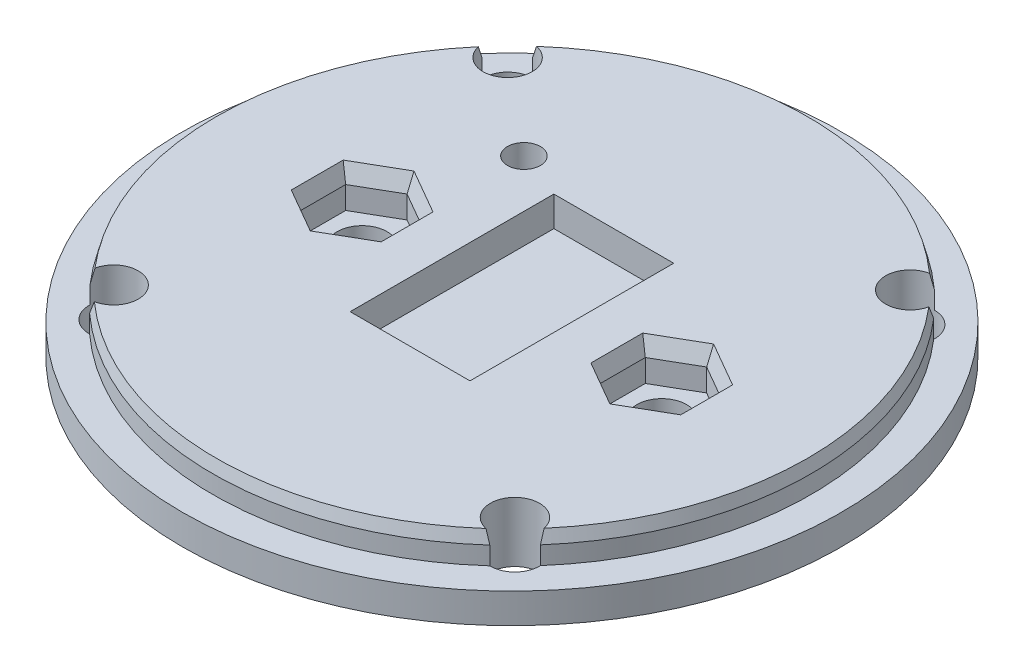
SolidWorks part; units mm, degrees
ref_plane "Спереди" through (0, 0, 0) normal (0, 0, 1) x (1, 0, 0)
ref_plane "Сверху" through (0, 0, 0) normal (0, 1, 0) x (1, 0, 0)
ref_plane "Справа" through (0, 0, 0) normal (1, 0, 0) x (0, 0, -1)
sketch "Эскиз1" plane through (0, 0, 0) normal (0, 1, 0) x (1, 0, 0)
  circle A0 centre (0, 0) radius 55
  dimension "D1" = 110
extrude "Бобышка-Вытянуть1" add sketch "Эскиз1" along normal blind 5
sketch "Эскиз2" plane through (0, 5, 0) normal (0, 1, 0) x (1, 0, 0)
  circle A0 centre (0, 0) radius 49.9
  dimension "D1" = 99.8
extrude "Бобышка-Вытянуть2" add sketch "Эскиз2" along normal blind 5
sketch "Эскиз3" plane through (0, 0, 0) normal (0, -1, 0) x (1, 0, 0)
  line L1 (17.5, -15) -> (-17.5, -15)
  line L2 (17.5, -15) -> (17.5, 15)
  line L3 (17.5, 15) -> (-17.5, 15)
  line L4 (-17.5, -15) -> (-17.5, 15)
  line L5 (17.5, -15) -> (-17.5, 15) construction
  line L6 (17.5, 15) -> (-17.5, -15) construction
  point P0 (0, 0)
  dimension "D1" = 35
  dimension "D2" = 30
extrude "Бобышка-Вытянуть3" add sketch "Эскиз3" along normal blind 25
sketch "Эскиз4" plane through (0, 0, 15) normal (0, 0, 1) x (1, 0, 0)
  line L0 (-17.5, 0) -> (17.5, -25) construction
  line L2 (10.1, -17.65) -> (-10.1, -17.65)
  line L3 (10.1, -17.65) -> (10.1, -7.35)
  line L4 (10.1, -7.35) -> (-10.1, -7.35)
  line L5 (-10.1, -17.65) -> (-10.1, -7.35)
  line L6 (10.1, -17.65) -> (-10.1, -7.35) construction
  line L7 (10.1, -7.35) -> (-10.1, -17.65) construction
  point P4 (0, -12.5)
  dimension "D1" = 20.2
  dimension "D2" = 10.3
extrude "Вырез-Вытянуть1" cut sketch "Эскиз4" against normal through all
sketch "Эскиз5" plane through (0, 0, 0) normal (0, -1, 0) x (1, 0, 0)
  line L0 (23.35, -22.85) -> (39.3102, -38.467) construction
  line L5 (-23.35, 22.85) -> (23.35, -22.85) construction
  line L6 (-23.35, -22.85) -> (23.35, 22.85) construction
  line L7 (-23.35, 22.85) -> (-39.3095, 38.4677) construction
  line L8 (23.35, 22.85) -> (39.1401, 38.6401) construction
  line L9 (-23.35, -22.85) -> (-39.3095, -38.4677) construction
  circle A0 centre (0, 0) radius 55 construction
  circle A1 centre (33.5922, -32.8719) radius 4.1
  circle A2 centre (-33.5917, -32.8724) radius 4.1
  circle A3 centre (-33.5917, 32.8724) radius 4.1
  circle A4 centre (33.4832, 32.9832) radius 4.1
  point P0 (0, 0)
  dimension "D3" = 8.2
  dimension "D1" = 46.7
  dimension "D2" = 45.7
  dimension "D4" = 8
  dimension "D5" = 8
  dimension "D6" = 8
  dimension "D7" = 8
extrude "Вырез-Вытянуть2" cut sketch "Эскиз5" against normal through all
sketch "Эскиз6" plane through (0, 10, 0) normal (0, 1, 0) x (1, 0, 0)
  line L0 (0, 0) -> (0.0004, 49.9) construction
  line L1 (0.0001, 20) -> (-17.9999, 20) construction
  arc A0 (33.5133, 36.9712) -> (-33.5128, 36.9717) centre (0, 0) ccw construction
  circle A1 centre (-17.9999, 20) radius 2.75
  dimension "D3" = 5.5
  dimension "D1" = 20
  dimension "D2" = 18
extrude "Вырез-Вытянуть3" cut sketch "Эскиз6" against normal through all
chamfer "Chamfer1" distance 2 angle 15 4 edges at (-0.0824, 10, 49.8999) (-49.9, 10, 0) (0.0004, 10, -49.9) (49.8999, 10, 0.0826)
sketch "Sketch2" plane through (0, -25, 0) normal (0, -1, 0) x (1, 0, 0)
  line L0 (17.5, 0) -> (-17.5, 0) construction
  line L1 (17.5, -15) -> (17.5, 15) construction
  line L2 (-17.5, 15) -> (-17.5, -15) construction
  line L4 (-17.5, -15) -> (17.5, -15)
  line L5 (-17.5, -15) -> (-17.5, 15)
  line L6 (-17.5, 15) -> (17.5, 15)
  line L7 (17.5, -15) -> (17.5, 15)
  line L8 (-17.5, -15) -> (17.5, 15) construction
  line L9 (-17.5, 15) -> (17.5, -15) construction
  point P6 (0, 0)
extrude "Cut-Extrude1" cut sketch "Sketch2" against normal blind 12.5
sketch "Sketch4" plane through (0, -7.35, 0) normal (0, -1, 0) x (1, 0, 0)
  line L1 (-35, -10) -> (35, -10)
  line L2 (-35, -10) -> (-35, 10)
  line L3 (-35, 10) -> (35, 10)
  line L4 (35, -10) -> (35, 10)
  line L5 (-35, -10) -> (35, 10) construction
  line L6 (-35, 10) -> (35, -10) construction
  point P0 (0, 0)
  dimension "D1" = 20
  dimension "D2" = 70
extrude "Boss-Extrude1" add sketch "Sketch4" against normal up to surface (5.35 mm away) from offset 2 up to face at (-17.9999, 0, -17.25) offset against normal yes
sketch "Sketch5" plane through (0, -5.35, 0) normal (0, -1, 0) x (1, 0, 0)
  line L0 (25, 10) -> (25, -10) construction
  line L1 (35, 10) -> (17.5, 10) construction
  line L2 (17.5, -10) -> (35, -10) construction
  line L3 (-25, 10) -> (-25, -10) construction
  line L4 (-17.5, 10) -> (-35, 10) construction
  line L5 (-35, -10) -> (-17.5, -10) construction
  circle A0 centre (25, 0) radius 4.15
  circle A1 centre (-25, 0) radius 4.15
  dimension "D1" = 8.3
  dimension "D2" = 50
  dimension "D3" = 25
extrude "Cut-Extrude2" cut sketch "Sketch5" against normal through all
sketch "Sketch6" plane through (0, 10, 0) normal (0, 1, 0) x (1, 0, 0)
  line L1 (-18.5048, 3.75) -> (-25, 7.5)
  line L2 (-25, 7.5) -> (-31.4952, 3.75)
  line L3 (-31.4952, 3.75) -> (-31.4952, -3.75)
  line L4 (-31.4952, -3.75) -> (-25, -7.5)
  line L5 (-25, -7.5) -> (-18.5048, -3.75)
  line L6 (-18.5048, -3.75) -> (-18.5048, 3.75)
  line L7 (31.4952, 3.75) -> (25, 7.5)
  line L8 (25, 7.5) -> (18.5048, 3.75)
  line L9 (18.5048, 3.75) -> (18.5048, -3.75)
  line L10 (18.5048, -3.75) -> (25, -7.5)
  line L11 (25, -7.5) -> (31.4952, -3.75)
  line L12 (31.4952, -3.75) -> (31.4952, 3.75)
  circle A0 centre (-25, 0) radius 7.5 construction
  circle A1 centre (25, 0) radius 7.5 construction
  dimension "D1" = 15
extrude "Cut-Extrude3" cut sketch "Sketch6" against normal blind 6.5
sketch "Sketch7" plane through (0, 10, 0) normal (0, 1, 0) x (1, 0, 0)
  line L1 (-10, -17) -> (10, -17)
  line L2 (-10, -17) -> (-10, 17)
  line L3 (-10, 17) -> (10, 17)
  line L4 (10, -17) -> (10, 17)
  line L5 (-10, -17) -> (10, 17) construction
  line L6 (-10, 17) -> (10, -17) construction
  point P0 (0, 0)
  dimension "D1" = 20
  dimension "D2" = 34
extrude "Cut-Extrude4" cut sketch "Sketch7" against normal blind 5
chamfer "Chamfer2" distance 1 angle 70 12 edges at (-28.2476, 10, -5.625) (-31.4952, 10, 0) (-28.2476, 10, 5.625) (-21.7524, 10, 5.625) (-18.5048, 10, 0) (-21.7524, 10, -5.625) (18.5048, 10, 0) (21.7524, 10, 5.625) (28.2476, 10, 5.625) (31.4952, 10, 0) (28.2476, 10, -5.625) (21.7524, 10, -5.625)
